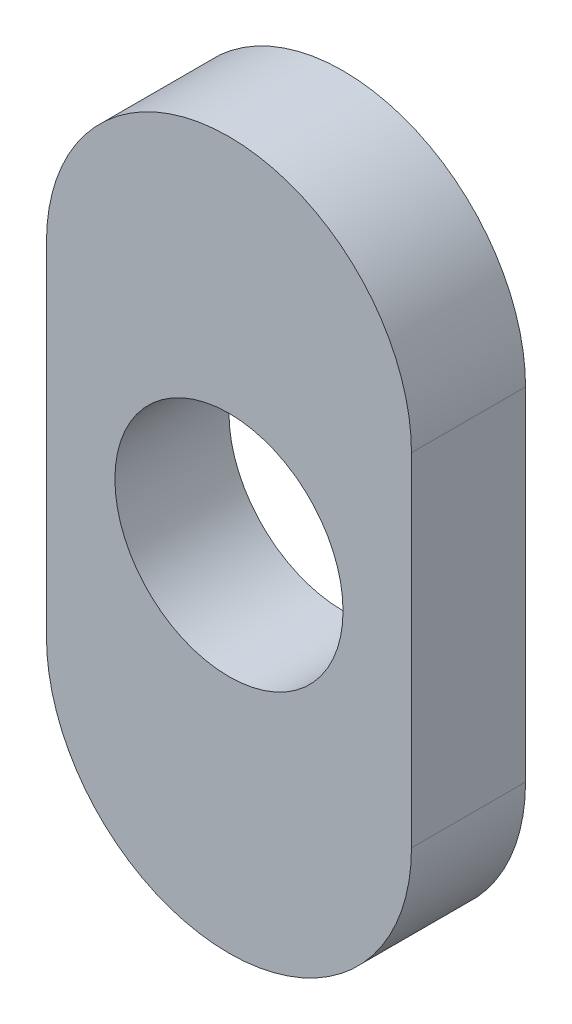
SolidWorks part; units mm, degrees
ref_plane "Plan de face" through (0, 0, 0) normal (0, 0, 1) x (1, 0, 0)
ref_plane "Plan de dessus" through (0, 0, 0) normal (0, 1, 0) x (1, 0, 0)
ref_plane "Plan de droite" through (0, 0, 0) normal (1, 0, 0) x (0, 0, -1)
sketch "Esquisse2" plane through (0, 0, 0) normal (0, 0, 1) x (1, 0, 0)
  line L0 (0, -7.5) -> (0, 7.5) construction
  line L7 (-8, -7.5) -> (-8, 7.5)
  line L8 (8, -7.5) -> (8, 7.5)
  arc A0 (-8, -7.5) -> (8, -7.5) centre (0, -7.5) ccw
  arc A1 (8, 7.5) -> (-8, 7.5) centre (0, 7.5) ccw
  point P2 (0, 0)
  dimension "D2" = 8
  dimension "40" = 15
extrude "Boss.-Extru.1" add sketch "Esquisse2" along normal blind 5
sketch "Esquisse3" plane through (0, 0, 5) normal (0, 0, 1) x (1, 0, 0)
  circle A0 centre (0, 0) radius 5
  dimension "D1" = 10
extrude "Enlèv. mat.-Extru.1" cut sketch "Esquisse3" against normal blind 10
